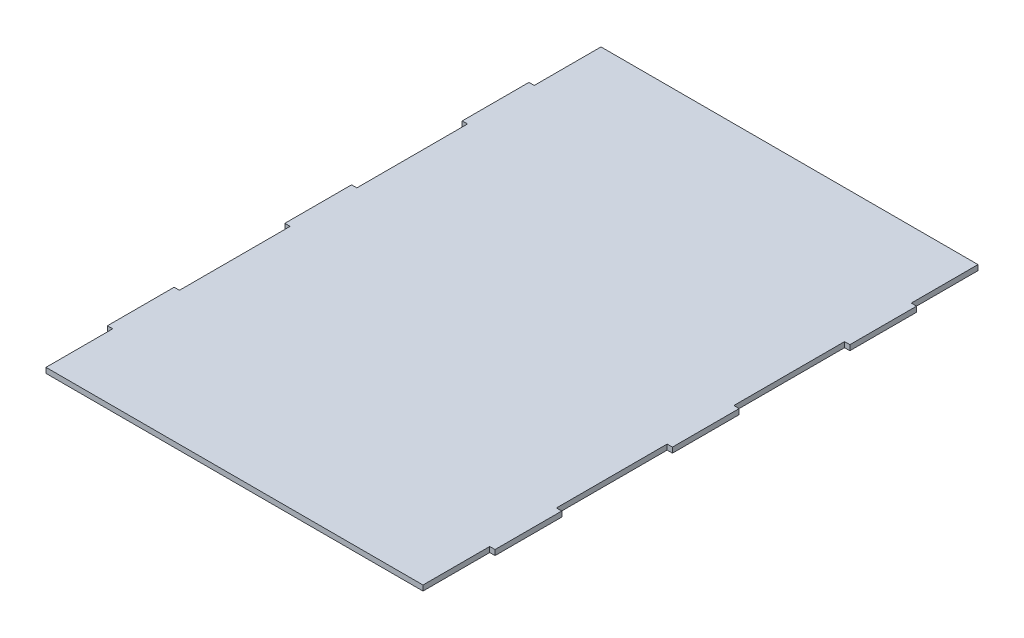
SolidWorks part; units mm, degrees
ref_plane "前视" through (0, 0, 0) normal (0, 0, 1) x (1, 0, 0)
ref_plane "上视" through (0, 0, 0) normal (0, 1, 0) x (1, 0, 0)
ref_plane "右视" through (0, 0, 0) normal (1, 0, 0) x (0, 0, -1)
sketch "Sketch1" plane through (0, 0, 0) normal (0, 1, 0) x (1, 0, 0)
  line L1 (0, 0) -> (226, 0)
  line L2 (0, 0) -> (0, -332.7)
  line L3 (0, -332.7) -> (226, -332.7)
  line L4 (226, 0) -> (226, -332.7)
  dimension "D1" = 332.7
  dimension "D2" = 226
extrude "Boss-Extrude1" add sketch "Sketch1" along normal blind 3.175
sketch "Sketch2" plane through (0, 3.175, 0) normal (0, 1, 0) x (1, 0, 0)
  line L0 (0, 0) -> (0, -332.7) construction
  line L1 (0, -40) -> (-3.175, -40)
  line L2 (0, -40) -> (0, -80)
  line L3 (0, -80) -> (-3.175, -80)
  line L4 (-3.175, -40) -> (-3.175, -80)
  line L5 (226, 0) -> (0, 0) construction
  line L6 (226, -332.7) -> (226, 0) construction
  line L7 (226, -40) -> (229.175, -40)
  line L8 (226, -40) -> (226, -80)
  line L9 (226, -80) -> (229.175, -80)
  line L10 (229.175, -40) -> (229.175, -80)
  dimension "D1" = 40
  dimension "D2" = 40
  dimension "D3" = 3.175
  dimension "D4" = 3.175
extrude "Boss-Extrude2" add sketch "Sketch2" against normal up to surface (3.175 mm away) up to face at (113, 0, 166.35)
pattern_linear "LPattern1" count 3 spacing 106.35 along (0, 0, 1) of "Boss-Extrude2"
